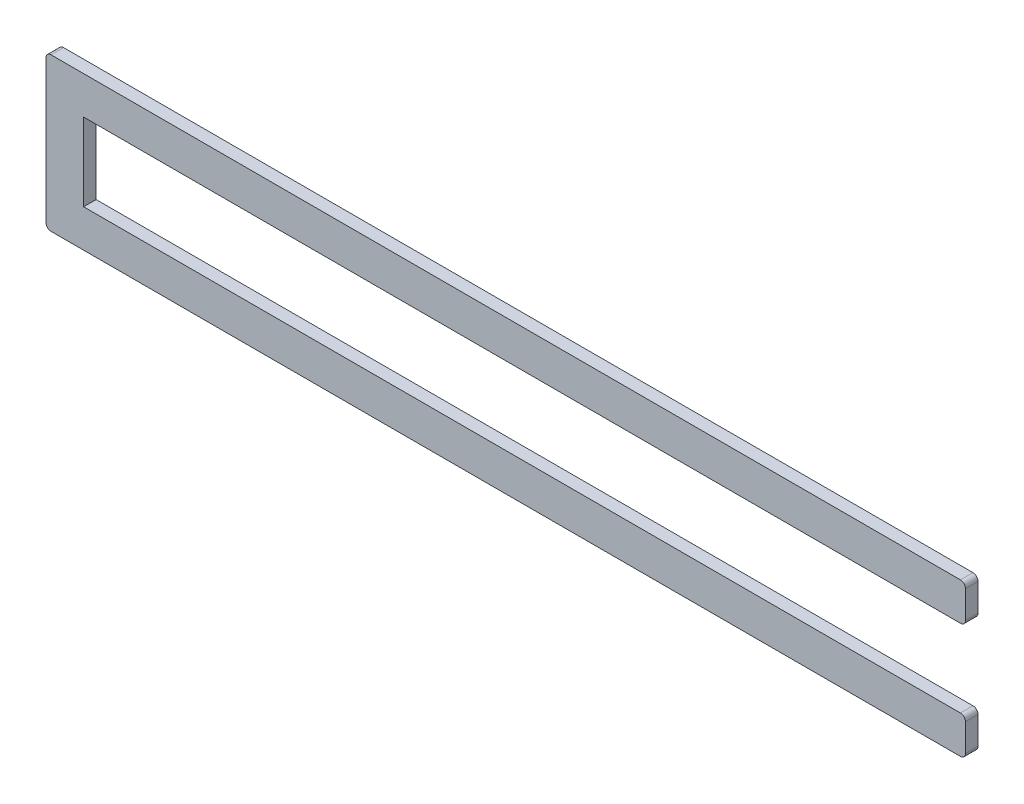
SolidWorks part; units mm, degrees
ref_plane "Alzado" through (0, 0, 0) normal (0, 0, 1) x (1, 0, 0)
ref_plane "Planta" through (0, 0, 0) normal (0, 1, 0) x (1, 0, 0)
ref_plane "Vista lateral" through (0, 0, 0) normal (1, 0, 0) x (0, 0, -1)
sketch "Croquis1" plane through (0, 0, 0) normal (0, 0, 1) x (1, 0, 0)
  line L1 (-8.795, -2.0974) -> (8.795, -2.0974)
  line L2 (-8.795, -2.0974) -> (-8.795, 2.0974)
  line L3 (-8.795, 2.0974) -> (8.795, 2.0974)
  line L4 (8.795, -2.0974) -> (8.795, 2.0974)
  line L5 (-8.795, -2.0974) -> (8.795, 2.0974) construction
  line L6 (-8.795, 2.0974) -> (8.795, -2.0974) construction
  point P0 (0, 0)
  dimension "D1" = 17.59
sketch "Croquis2" plane through (0, 0, 0) normal (0, 0, 1) x (1, 0, 0)
  line L0 (-242.443, -38.735) -> (-242.443, 38.735)
  line L1 (-223.393, -19.685) -> (223.393, -19.685) construction
  line L2 (-223.393, -19.685) -> (-223.393, 19.685) construction
  line L3 (-223.393, 19.685) -> (223.393, 19.685) construction
  line L4 (223.393, -19.685) -> (223.393, 19.685)
  line L5 (-223.393, -19.685) -> (223.393, 19.685) construction
  line L6 (-223.393, 19.685) -> (223.393, -19.685) construction
  line L7 (-242.443, 38.735) -> (223.393, 38.735)
  line L9 (-242.443, -38.735) -> (223.393, -38.735)
  line L10 (223.393, 19.685) -> (223.393, 38.735)
  line L11 (223.393, -19.685) -> (223.393, -38.735)
  line L12 (-242.443, 38.735) -> (242.443, 38.735) construction
  line L13 (242.443, -38.735) -> (242.443, 38.735) construction
  line L14 (-242.443, -38.735) -> (242.443, -38.735) construction
  point P0 (0, 0)
  dimension "D1" = 446.786
  dimension "D2" = 39.37
  dimension "D4" = 19.05
  dimension "D3" = 19.05
extrude "Saliente-Extruir1" add sketch "Croquis2" along normal blind 6.35
sketch "Croquis3" plane through (0, 0, 6.35) normal (0, 0, 1) x (1, 0, 0)
  line L0 (223.393, -38.735) -> (223.393, 38.735) construction
  line L1 (223.393, -19.685) -> (-223.393, -19.685)
  line L2 (223.393, -19.685) -> (223.393, 19.685)
  line L3 (223.393, 19.685) -> (-223.393, 19.685)
  line L4 (-223.393, -19.685) -> (-223.393, 19.685)
  line L5 (0, 0) -> (223.393, 0) construction
  line L6 (-242.443, 38.735) -> (-242.443, -38.735) construction
  line L7 (-242.443, -38.735) -> (223.393, -38.735) construction
  dimension "D1" = 19.05
  dimension "D2" = 446.786
  dimension "D3" = 19.05
  dimension "D4" = 39.37
extrude "Cortar-Extruir1" cut sketch "Croquis3" against normal through all
sketch "Croquis4" [suppressed] plane through (0, 0, 6.35) normal (0, 0, 1) x (1, 0, 0)
  line L0 (-9.525, 38.735) -> (-9.525, -38.735) construction
  line L1 (223.393, 38.735) -> (-242.443, 38.735) construction
  line L2 (-242.443, -38.735) -> (223.393, -38.735) construction
  line L3 (-217.17, 38.735) -> (-217.17, -38.735) construction
  line L4 (-242.443, 38.735) -> (-242.443, -38.735) construction
  line L5 (-242.443, 0) -> (223.393, 0) construction
  line L6 (223.393, -38.735) -> (223.393, 38.735) construction
  line L7 (-217.17, 16.3115) -> (-217.17, 11.049) construction
  line L8 (-217.17, -11.049) -> (-217.17, -16.3115) construction
  circle A0 centre (-217.17, 13.6802) radius 2.6312
  circle A1 centre (-217.17, -13.6802) radius 2.6312
  circle A2 centre (217.17, -13.6802) radius 2.6312
  circle A3 centre (217.17, 13.6802) radius 2.6312
  circle A4 centre (-74.422, 13.6802) radius 2.6313
  circle A5 centre (-74.422, -13.6802) radius 2.6313
  circle A6 centre (74.422, 13.6802) radius 2.6313
  circle A7 centre (74.422, -13.6802) radius 2.6313
  point P24 (-9.525, 0)
  dimension "D2" = 5.2625
  dimension "D1" = 25.273
  dimension "D3" = 22.098
  dimension "D4" = 142.748
  dimension "D5" = 142.748
  dimension "D6" = 148.844
  dimension "D7" = 6.223
  dimension "D8" = 27.3605
  dimension "D9" = 27.3605
extrude "Cortar-Extruir2" [suppressed] cut sketch "Croquis4" against normal through all
sketch "Croquis5" [suppressed] plane through (0, 0, 6.35) normal (0, 0, 1) x (1, 0, 0)
  line L0 (223.393, 19.685) -> (-223.393, 19.685) construction
  line L1 (223.393, -38.735) -> (223.393, 38.735) construction
  line L2 (-223.393, 19.685) -> (-223.393, -19.685) construction
  line L3 (-223.393, -19.685) -> (223.393, -19.685) construction
  line L4 (223.393, 38.735) -> (-242.443, 38.735) construction
  line L5 (-242.443, -38.735) -> (223.393, -38.735) construction
  line L6 (-242.443, 38.735) -> (-242.443, -38.735) construction
  line L7 (0, 38.735) -> (0, 19.685) construction
  line L8 (-223.393, 19.685) -> (-223.393, 38.735) construction
  line L9 (-223.393, 29.21) -> (223.393, 29.21) construction
  line L10 (-223.393, 0) -> (223.393, 0) construction
  circle A0 centre (-210.693, 29.21) radius 3.5
  circle A1 centre (-70.993, 29.21) radius 3.5
  circle A2 centre (68.707, 29.21) radius 3.5
  circle A3 centre (208.407, 29.21) radius 3.5
  circle A4 centre (208.407, -29.21) radius 3.5
  circle A5 centre (68.707, -29.21) radius 3.5
  circle A6 centre (-70.993, -29.21) radius 3.5
  circle A7 centre (-210.693, -29.21) radius 3.5
  dimension "D4" = 7
  dimension "D1" = 19.05
  dimension "D2" = 19.05
  dimension "D3" = 19.05
  dimension "D5" = 12.7
  dimension "D7" = 139.7
  dimension "D6" = 4
extrude "Cortar-Extruir3" [suppressed] cut sketch "Croquis5" against normal through all
fillet "Redondeo1" [suppressed] radius 2.54
fillet "Redondeo2" radius 2.54 6 edges at (-242.443, -38.735, 3.175) (-242.443, 38.735, 3.175) (223.393, -38.735, 3.175) (223.393, -19.685, 3.175) (223.393, 19.685, 3.175) (223.393, 38.735, 3.175)
